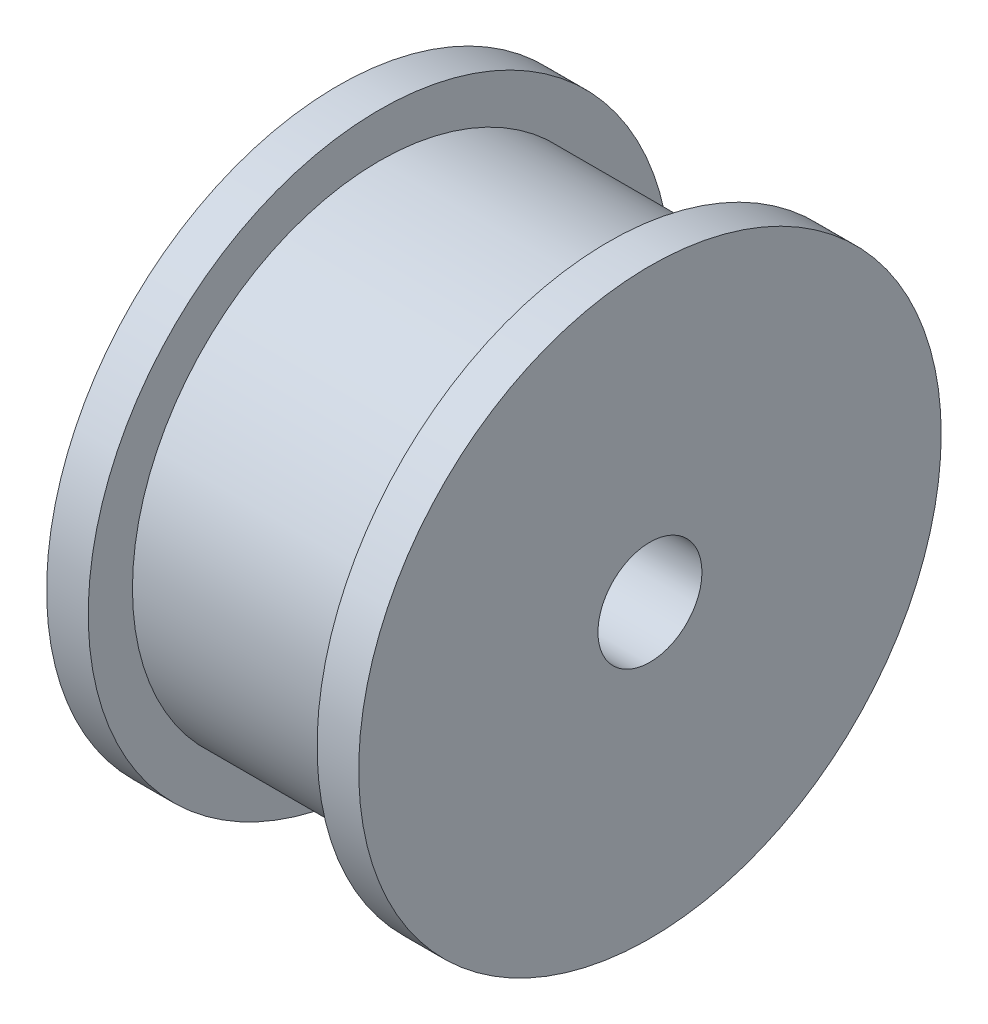
SolidWorks part; units mm, degrees
ref_plane "Front Plane" through (0, 0, 0) normal (0, 0, 1) x (1, 0, 0)
ref_plane "Top Plane" through (0, 0, 0) normal (0, 1, 0) x (1, 0, 0)
ref_plane "Right Plane" through (0, 0, 0) normal (1, 0, 0) x (0, 0, -1)
sketch "Sketch1" plane through (0, 0, 0) normal (1, 0, 0) x (0, 0, -1)
  circle A0 centre (0, 0) radius 14
  dimension "D1" = 28
extrude "Boss-Extrude1" add sketch "Sketch1" along normal blind 2
sketch "Sketch2" plane through (2, 0, 0) normal (1, 0, 0) x (0, 0, -1)
  circle A0 centre (0, 0) radius 11.875
  dimension "D1" = 23.75
extrude "Boss-Extrude2" add sketch "Sketch2" along normal blind 11
sketch "Sketch3" plane through (13, 0, 0) normal (1, 0, 0) x (0, 0, -1)
  circle A0 centre (0, 0) radius 14
  dimension "D1" = 28
extrude "Boss-Extrude3" add sketch "Sketch3" along normal blind 2
sketch "Sketch4" plane through (15, 0, 0) normal (1, 0, 0) x (0, 0, -1)
  circle A0 centre (0, 0) radius 2.5
  dimension "D1" = 5
extrude "Cut-Extrude1" cut sketch "Sketch4" against normal through all
equation "\"D1@Sketch3\"=\"D1@Sketch1\""
